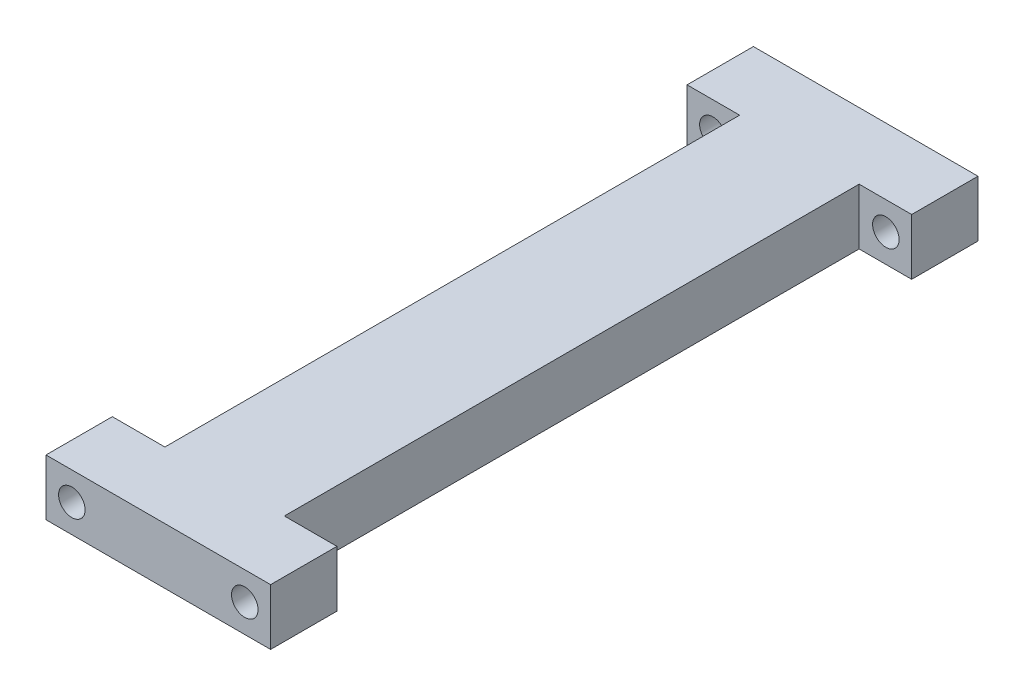
SolidWorks part; units mm, degrees
ref_plane "Front Plane" through (0, 0, 0) normal (0, 0, 1) x (1, 0, 0)
ref_plane "Top Plane" through (0, 0, 0) normal (0, 1, 0) x (1, 0, 0)
ref_plane "Right Plane" through (0, 0, 0) normal (1, 0, 0) x (0, 0, -1)
sketch "Sketch7" plane through (0, 0, 0) normal (0, 1, 0) x (1, 0, 0)
  line L0 (-12.7, -32.5) -> (-12.7, -40)
  line L1 (-12.7, 40) -> (12.7, 40)
  line L2 (-12.7, 40) -> (-12.7, 32.5)
  line L3 (-12.7, -40) -> (12.7, -40)
  line L4 (12.7, 40) -> (12.7, 32.5)
  line L5 (-12.7, 32.5) -> (-6.7564, 32.5)
  line L7 (-12.7, -32.5) -> (-6.7564, -32.5)
  line L8 (-6.7564, 32.5) -> (-6.7564, -32.5)
  line L9 (12.7, 32.5) -> (6.7564, 32.5)
  line L11 (12.7, -32.5) -> (6.7564, -32.5)
  line L12 (6.7564, 32.5) -> (6.7564, -32.5)
  line L13 (12.7, -32.5) -> (12.7, -40)
  point P12 (0, 40)
  point P14 (6.7564, 0)
  dimension "D1" = 25.4
  dimension "D2" = 7.5
  dimension "D3" = 80
  dimension "D4" = 5.9436
extrude "Boss-Extrude3" add sketch "Sketch7" along normal mid plane 6.35
hole_wizard "Ø3.0mm Dowel Hole1" positions "Sketch9" profile "Sketch10" hole size "Ø3.0" standard "ANSI Metric" end condition through all
sketch "Sketch9" plane through (0, 0, -40) normal (0, 0, -1) x (-1, 0, 0)
  line L0 (-9.779, 0) -> (9.779, 0) construction
  point P0 (-9.779, 0)
  point P2 (9.779, 0)
  point P11 (0, 0)
  dimension "D1" = 19.558
sketch "Sketch10" plane through (9.779, 0, -40) normal (1, 0, 0) x (0, 1, 0)
  line L0 (0, 0) -> (0, 80)
  line L1 (0, 80) -> (1.5, 80)
  line L2 (1.5, 80) -> (1.5, 0)
  line L5 (1.5, 0) -> (0, 0)
  line L11 (0, -6.35) -> (0, 107.95) construction
  dimension "Thru Hole Dia." = 3
  dimension "Thru Hole Depth" = 80
